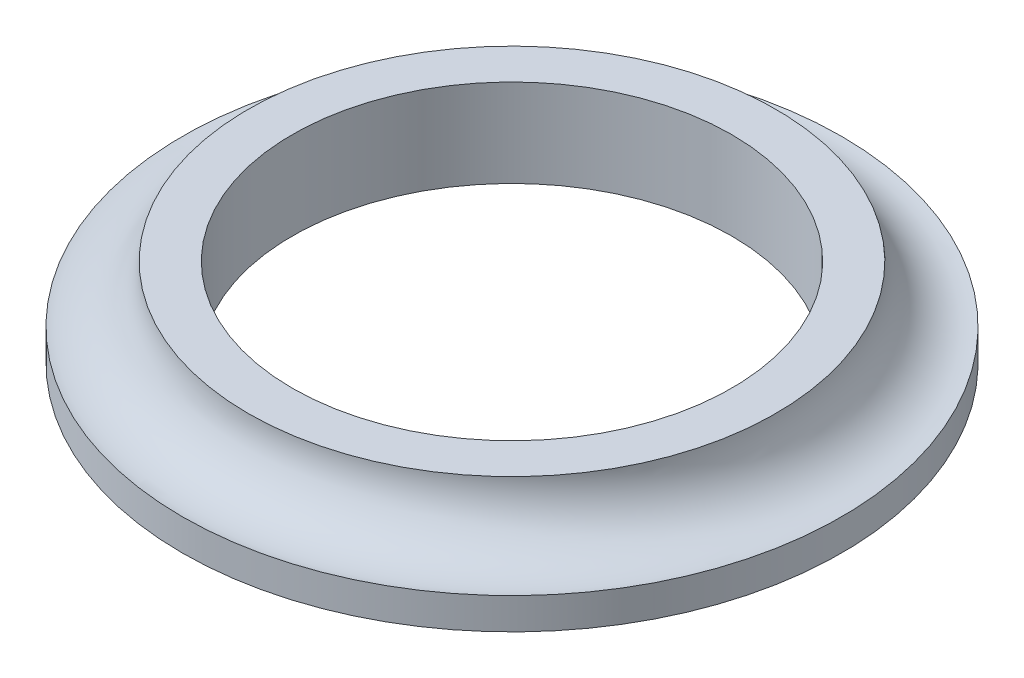
SolidWorks part; units mm, degrees
material "AISI 316 Stainless Steel Sheet (SS)"
ref_plane "Front Plane" through (0, 0, 0) normal (0, 0, 1) x (1, 0, 0)
ref_plane "Top Plane" through (0, 0, 0) normal (0, 1, 0) x (1, 0, 0)
ref_plane "Right Plane" through (0, 0, 0) normal (1, 0, 0) x (0, 0, -1)
sketch "Sketch1" plane through (0, 0, 0) normal (1, 0, 0) x (0, 0, -1)
  line L0 (0, 212.0099) -> (0, -221.795) construction
  line L1 (-72.5374, 0) -> (78.2117, 0) construction
  line L2 (-25, 5.4239) -> (-25, -4.5761)
  line L3 (-25, -4.5761) -> (-37.5, -4.5761)
  line L4 (-37.5, -4.5761) -> (-37.5, -0.9987)
  line L5 (-25, 5.4239) -> (-30, 5.4239)
  line L6 (-30, 15.2843) -> (-30, 5.4239) construction
  arc A1 (-37.5, -0.9987) -> (-30, 5.4239) centre (-36.5, 5.4239) ccw
  dimension "D1" = 50
  dimension "D4" = 6.5
  dimension "D2" = 75
  dimension "D3" = 10
  dimension "D5" = 30
revolve "Revolve1" add sketch "Sketch1" angle 360 about L0
